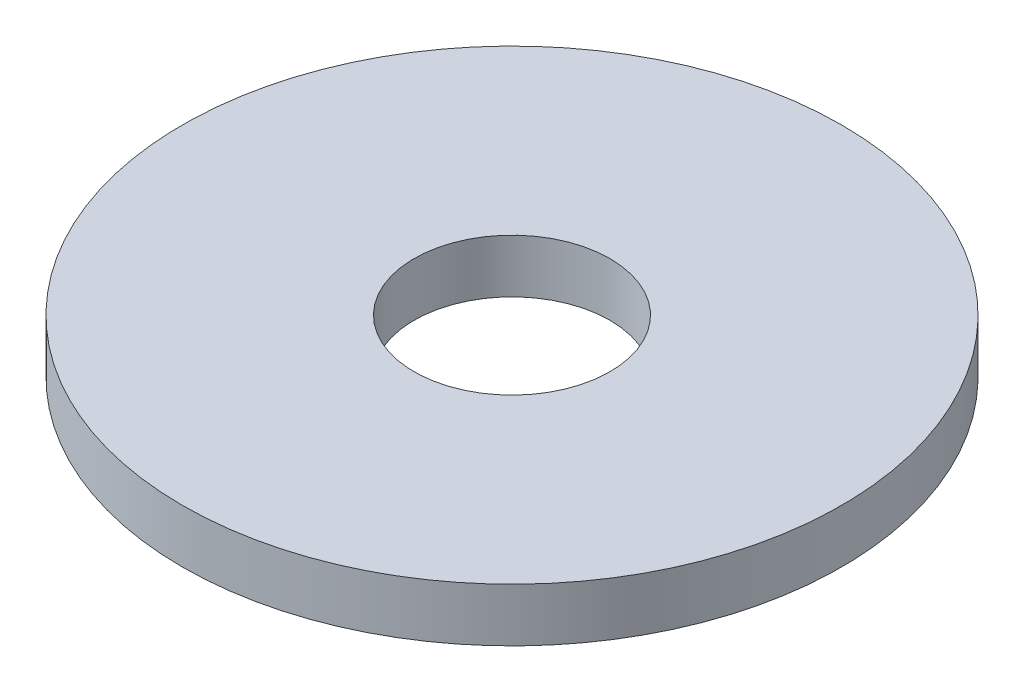
SolidWorks part; units mm, degrees
ref_plane "前视基准面" through (0, 0, 0) normal (0, 0, 1) x (1, 0, 0)
ref_plane "上视基准面" through (0, 0, 0) normal (0, 1, 0) x (1, 0, 0)
ref_plane "右视基准面" through (0, 0, 0) normal (1, 0, 0) x (0, 0, -1)
sketch "草图1" plane through (0, 0, 0) normal (0, 0, 1) x (1, 0, 0)
  line L10 (0, 0) -> (0, 0.85) construction
  line L12 (5.5, 0) -> (18.5, 0)
  line L13 (5.5, 0) -> (5.5, 3)
  line L14 (5.5, 3) -> (18.5, 3)
  line L15 (18.5, 0) -> (18.5, 3)
  dimension "d1" = 11
  dimension "d2" = 37
  dimension "h" = 3
sketch "草图2" plane through (0, 0, 0) normal (0, 0, 1) x (1, 0, 0)
  line L1 (0, 0) -> (0, 1.8517) construction
  line L10 (5.5, 0) -> (18.5, 0)
  line L11 (18.5, 0) -> (18.5, 3)
  line L12 (18.5, 3) -> (5.5, 3)
  line L13 (5.5, 3) -> (5.5, 0)
  line L14 (5.5, 0) -> (18.5, 0)
  line L15 (18.5, 0) -> (18.5, 3)
  line L16 (18.5, 3) -> (5.5, 3)
  line L17 (5.5, 3) -> (5.5, 0)
  dimension "D1" = 0
revolve "旋转1" add sketch "草图2" angle 360 about L1
